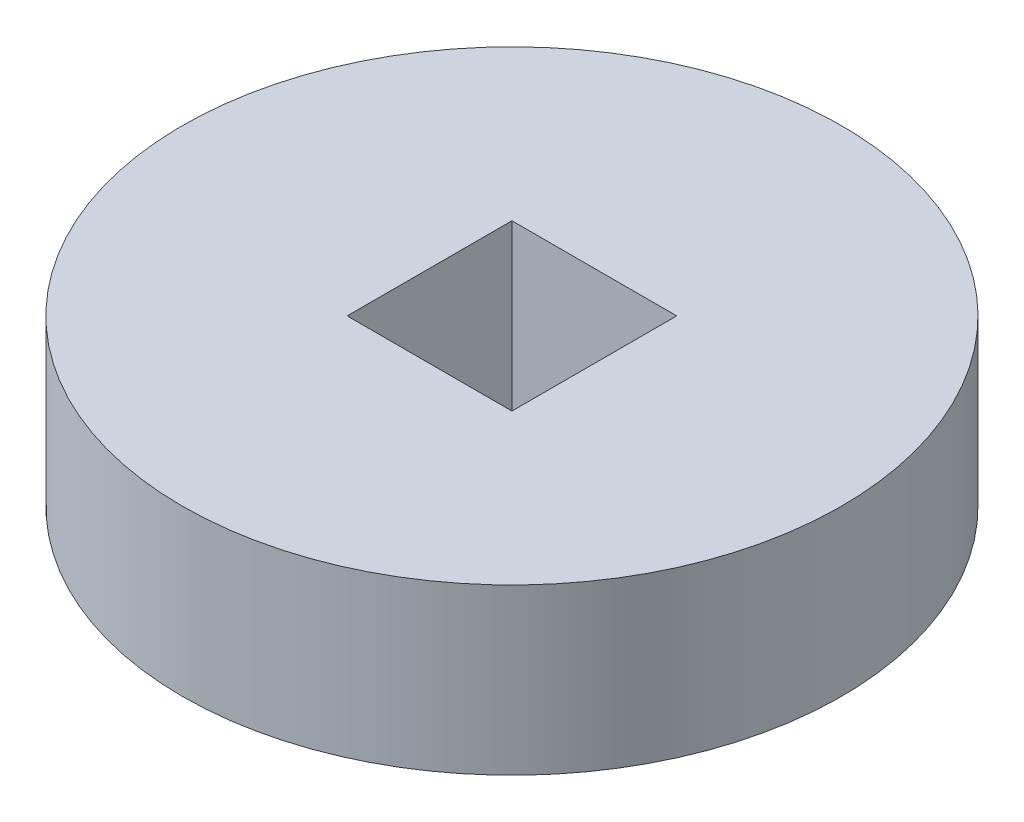
SolidWorks part; units mm, degrees
ref_plane "Front Plane" through (0, 0, 0) normal (0, 0, 1) x (1, 0, 0)
ref_plane "Top Plane" through (0, 0, 0) normal (0, 1, 0) x (1, 0, 0)
ref_plane "Right Plane" through (0, 0, 0) normal (1, 0, 0) x (0, 0, -1)
sketch "Belt Pulley" plane through (0, 0, 0) normal (0, 1, 0) x (1, 0, 0)
  line L1 (-3.175, -3.175) -> (3.175, -3.175)
  line L2 (-3.175, -3.175) -> (-3.175, 3.175)
  line L3 (-3.175, 3.175) -> (3.175, 3.175)
  line L4 (3.175, -3.175) -> (3.175, 3.175)
  line L5 (-3.175, -3.175) -> (3.175, 3.175) construction
  line L6 (-3.175, 3.175) -> (3.175, -3.175) construction
  circle A0 centre (0, 0) radius 12.7
  dimension "D1" = 25.4
  dimension "D2" = 6.35
  dimension "D3" = 6.35
extrude "Boss-Extrude1" add sketch "Belt Pulley" along normal blind 6.35 contours A0 L4 L1 L2 L3
equation "\"Ball Diameter\"= 1.75in"
equation "\"Sheet Thickness\"= 0.25in"
equation "\"Screw Diameter\"= .17in"
equation "\"Robot Diameter\"= 16in"
equation "\"Castor Screw Diameter\"= 0.22in"
equation "\"Wheel Diameter\" = 4in"
equation "\"Nut Diameter\" = 8.4mm"
equation "\"Nut Height\" = 2.9mm"
equation "\"Screw Height\" = 0.55in"
equation "\"Pulley Diameter\" = 1in"
equation "\"Reactor Height\" = 14in"
equation "\"D1@Belt Pulley\"=\"Pulley Diameter\""
equation "\"D2@Belt Pulley\"=\"Sheet Thickness\""
equation "\"D3@Belt Pulley\"=\"Sheet Thickness\""
equation "\"D1@Boss-Extrude1\"=\"Sheet Thickness\""
